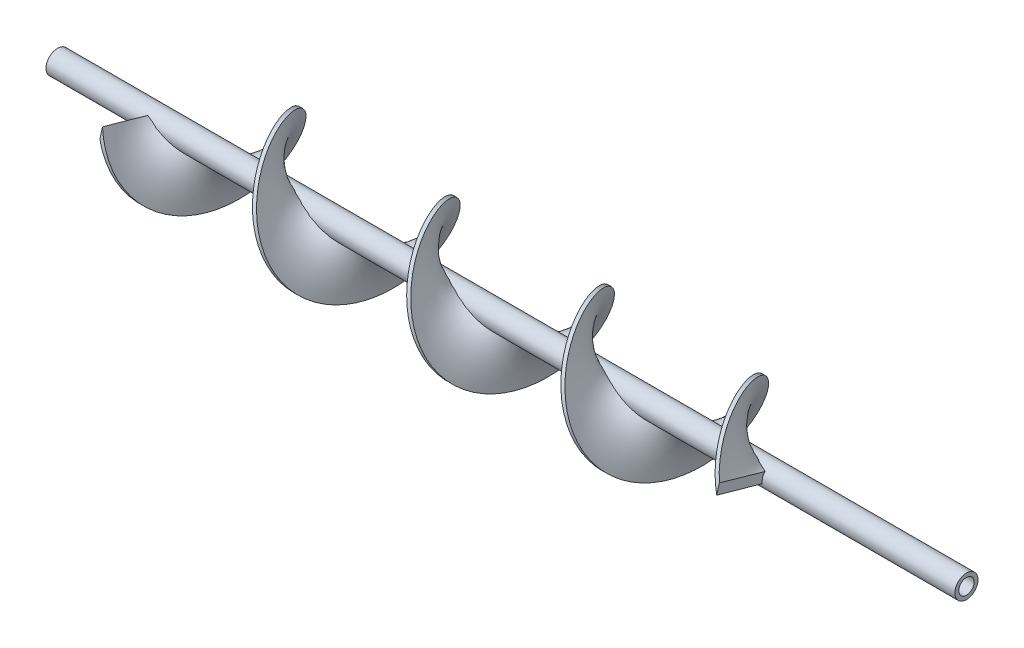
SolidWorks part; units mm, degrees
material "Brass"
ref_plane "Vorderansicht" through (0, 0, 0) normal (0, 0, 1) x (1, 0, 0)
ref_plane "Draufsicht" through (0, 0, 0) normal (0, 1, 0) x (1, 0, 0)
ref_plane "Seitenansicht" through (0, 0, 0) normal (1, 0, 0) x (0, 0, -1)
sketch "Skizze3" plane through (0, 0, 0) normal (1, 0, 0) x (0, 0, -1)
  circle A0 centre (0, 0) radius 6
  circle A1 centre (0, 0) radius 4
  dimension "D1" = 12
  dimension "D2" = 2
extrude "Aufsatz-Linear austragen1" add sketch "Skizze3" against normal blind 415 and the other way blind 51.5 separate body
ref_plane "Ref_of_Spiral" through (36.5, 0, 0) normal (1, 0, 0) x (0, 0, -1)
sketch "Skizze1" plane through (36.5, 0, 0) normal (1, 0, 0) x (0, 0, -1)
  circle A0 centre (0, 0) radius 4
  dimension "D1" = 8
curve "Spirale/Helix1" pitch 80 height 320 turns 4
sketch "Skizze2" plane through (0, 0, 0) normal (1, 0, 0) x (0, 0, -1)
  line L0 (19.3938, 0) -> (56.2084, 0) construction
  line L2 (3.1225, -2.5) -> (30, -2.5)
  line L4 (3.1225, 2.5) -> (30, 2.5)
  line L5 (30, -2.5) -> (30, 2.5)
  arc A1 (3.1225, -2.5) -> (3.1225, 2.5) centre (0, 0) ccw
  dimension "D1" = 30
  dimension "D3" = 5
sweep "Austragung1" add profiles "Skizze2" path "Spirale/Helix1"
sketch "Sketch1" plane through (51.5, 0, 0) normal (1, 0, 0) x (0, 0, -1)
  circle A0 centre (0, 0) radius 4
  circle A1 centre (0, 0) radius 6
extrude "Boss-Extrude1" add sketch "Sketch1" along normal blind 65
sketch "Sketch2" plane through (-415, 0, 0) normal (-1, 0, 0) x (0, 0, 1)
  circle A0 centre (0, 0) radius 6
extrude "Cut-Extrude1" cut sketch "Sketch2" against normal blind 80
sketch "Sketch3" plane through (116.5, 0, 0) normal (1, 0, 0) x (0, 0, -1)
  circle A0 centre (0, 0) radius 6
  circle A1 centre (0, 0) radius 4
extrude "Boss-Extrude2" add sketch "Sketch3" along normal blind 20
